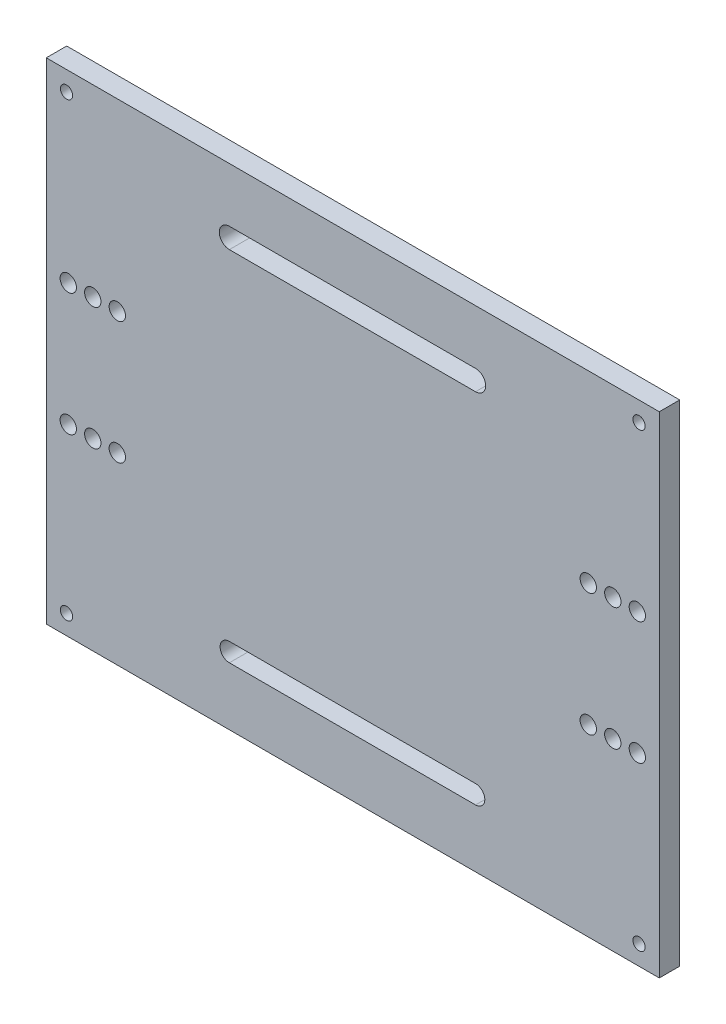
SolidWorks part; units mm, degrees
material "Acrylic (Medium-high impact)"
ref_plane "Front Plane" through (0, 0, 0) normal (0, 0, 1) x (1, 0, 0)
ref_plane "Top Plane" through (0, 0, 0) normal (0, 1, 0) x (1, 0, 0)
ref_plane "Right Plane" through (0, 0, 0) normal (1, 0, 0) x (0, 0, -1)
sketch "Model" plane through (0, 0, 0) normal (0, 0, 1) x (1, 0, 0)
  line L0 (15.051, 18.6809) -> (165.051, 18.6809)
  line L1 (165.051, 18.6809) -> (165.051, 138.6809)
  line L2 (165.051, 138.6809) -> (15.051, 138.6809)
  line L3 (15.051, 138.6809) -> (15.051, 18.6809)
  line L4 (60.0514, 124.9773) -> (120.051, 125.1884)
  line L5 (120.051, 120.1884) -> (60.051, 120.1884)
  line L6 (60.0514, 32.3844) -> (120.051, 32.1733)
  line L7 (120.051, 37.1733) -> (60.051, 37.1733)
  circle A0 centre (20.4274, 93.6809) radius 2
  circle A1 centre (26.4274, 93.6809) radius 2
  circle A2 centre (32.4274, 93.6809) radius 2
  circle A3 centre (20.4274, 63.6809) radius 2
  circle A4 centre (26.4274, 63.6809) radius 2
  circle A5 centre (32.4274, 63.6809) radius 2
  circle A6 centre (159.6747, 93.6809) radius 2
  circle A7 centre (153.6747, 93.6809) radius 2
  circle A8 centre (147.6747, 93.6809) radius 2
  circle A9 centre (159.6747, 63.6809) radius 2
  circle A10 centre (153.6747, 63.6809) radius 2
  circle A11 centre (147.6747, 63.6809) radius 2
  circle A12 centre (20.0057, 133.9073) radius 1.5
  circle A13 centre (160.0964, 133.9073) radius 1.5
  circle A14 centre (20.0057, 23.4544) radius 1.5
  circle A15 centre (160.0964, 23.4544) radius 1.5
  arc A16 (120.051, 120.1884) -> (120.051, 125.1884) centre (120.0598, 122.6884) ccw
  arc A17 (60.0342, 124.9773) -> (60.051, 120.1884) centre (60.051, 122.5829) ccw
  arc A18 (120.051, 32.1733) -> (120.051, 37.1733) centre (120.0598, 34.6733) ccw
  arc A19 (60.051, 37.1733) -> (60.0342, 32.3845) centre (60.051, 34.7789) ccw
extrude "Boss-Extrude1" add sketch "Model" along normal blind 5
sketch "Sketch3" plane through (0, 0, 5) normal (0, 0, 1) x (1, 0, 0)
  line L0 (59.8485, 122.906) -> (120.0876, 122.906) construction
  line L1 (59.8485, 125.3792) -> (120.0876, 125.3792)
  line L2 (59.8485, 120.4329) -> (120.0876, 120.4329)
  line L3 (59.8485, 35.1439) -> (120.0876, 35.1439) construction
  line L4 (59.8485, 37.4116) -> (120.0876, 37.4116)
  line L5 (59.8485, 32.8763) -> (120.0876, 32.8763)
  arc A0 (59.8485, 125.3792) -> (59.8485, 120.4329) centre (59.8485, 122.906) ccw
  arc A1 (120.0876, 120.4329) -> (120.0876, 125.3792) centre (120.0876, 122.906) ccw
  arc A2 (59.8485, 37.4116) -> (59.8485, 32.8763) centre (59.8485, 35.1439) ccw
  arc A3 (120.0876, 32.8763) -> (120.0876, 37.4116) centre (120.0876, 35.1439) ccw
  point P2 (89.9681, 122.906)
  point P7 (89.9681, 35.1439)
extrude "Cut-Extrude1" cut sketch "Sketch3" against normal through all
